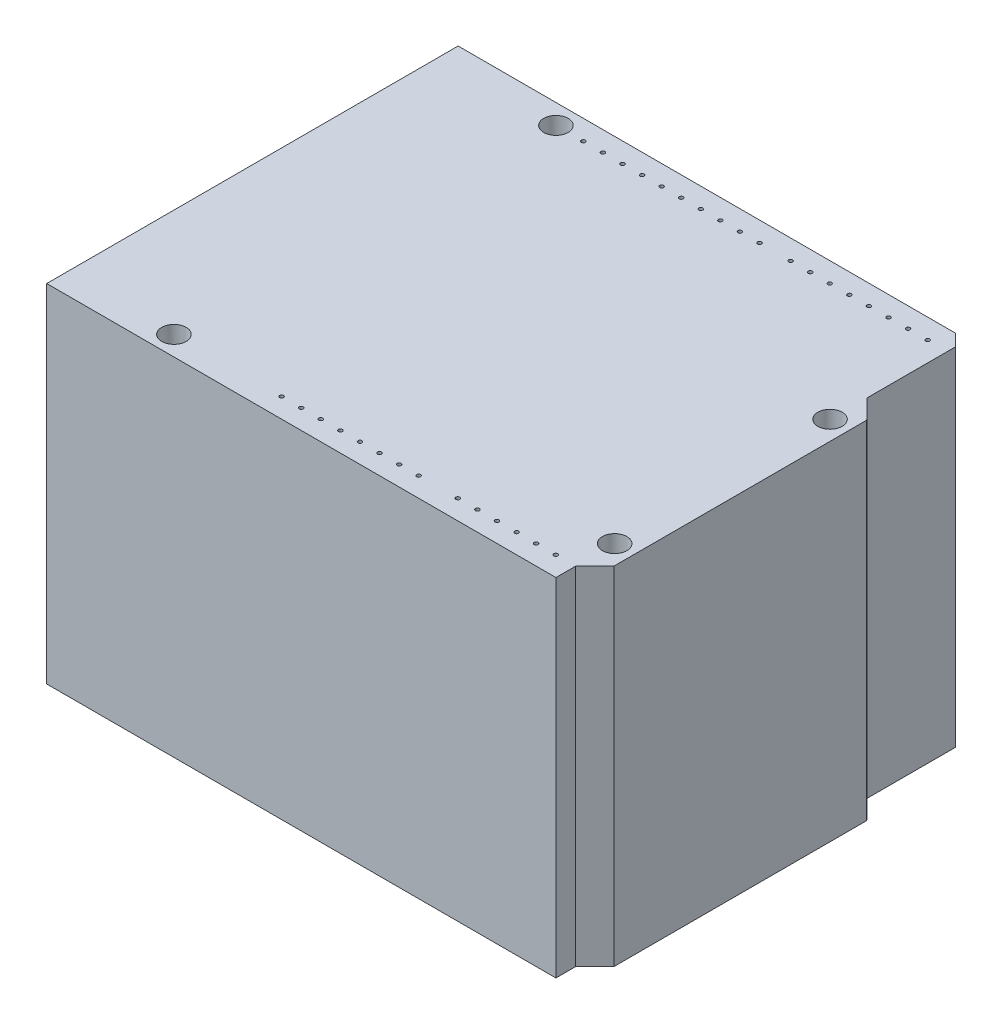
SolidWorks part; units mm, degrees
ref_plane "Alzado" through (0, 0, 0) normal (0, 0, 1) x (1, 0, 0)
ref_plane "Planta" through (0, 0, 0) normal (0, 1, 0) x (1, 0, 0)
ref_plane "Vista lateral" through (0, 0, 0) normal (1, 0, 0) x (0, 0, -1)
sketch "Board" plane through (0, 0, 0) normal (0, 1, 0) x (1, 0, 0)
  line L0 (68.55, 37.846) -> (68.55, 5.08)
  line L1 (66.07, 0) -> (0, 0)
  line L2 (66.07, 51.8137) -> (66.07, 40.386)
  line L3 (66.07, 0) -> (66.07, 2.54)
  line L4 (66.07, 40.386) -> (68.55, 37.846)
  line L5 (68.55, 5.08) -> (66.07, 2.54)
  line L6 (0, 0) -> (0, 53.3785)
  line L7 (64.5052, 53.3785) -> (0, 53.3785)
  line L8 (66.07, 51.8137) -> (64.5052, 53.3785)
sketch "Drills" plane through (0, 0, 0) normal (0, 1, 0) x (1, 0, 0)
  line L0 (13.97, 2.54) -> (63.5, 2.54) construction
  line L2 (15.27, 50.8) -> (63.5, 50.8) construction
  circle A0 centre (15.27, 50.8) radius 1.5875
  circle A1 centre (66.07, 35.56) radius 1.5875
  circle A2 centre (66.07, 7.62) radius 1.5875
  circle A3 centre (13.97, 2.54) radius 1.5875
sketch "Pinout" plane through (0, 0, 0) normal (0, 1, 0) x (1, 0, 0)
  circle A0 centre (63.5, 2.54) radius 0.254
  circle A1 centre (60.96, 2.54) radius 0.254
  circle A2 centre (58.42, 2.54) radius 0.254
  circle A3 centre (55.88, 2.54) radius 0.254
  circle A4 centre (53.34, 2.54) radius 0.254
  circle A5 centre (50.8, 2.54) radius 0.254
  circle A6 centre (45.72, 2.54) radius 0.254
  circle A7 centre (43.18, 2.54) radius 0.254
  circle A8 centre (40.64, 2.54) radius 0.254
  circle A9 centre (38.1, 2.54) radius 0.254
  circle A10 centre (35.56, 2.54) radius 0.254
  circle A11 centre (33.02, 2.54) radius 0.254
  circle A12 centre (30.48, 2.54) radius 0.254
  circle A13 centre (27.94, 2.54) radius 0.254
  circle A14 centre (63.5, 50.8) radius 0.254
  circle A15 centre (60.96, 50.8) radius 0.254
  circle A16 centre (58.42, 50.8) radius 0.254
  circle A17 centre (55.88, 50.8) radius 0.254
  circle A18 centre (53.34, 50.8) radius 0.254
  circle A19 centre (50.8, 50.8) radius 0.254
  circle A20 centre (48.26, 50.8) radius 0.254
  circle A21 centre (45.72, 50.8) radius 0.254
  circle A22 centre (41.686, 50.8) radius 0.254
  circle A23 centre (39.146, 50.8) radius 0.254
  circle A24 centre (36.606, 50.8) radius 0.254
  circle A25 centre (34.066, 50.8) radius 0.254
  circle A26 centre (31.526, 50.8) radius 0.254
  circle A27 centre (28.986, 50.8) radius 0.254
  circle A28 centre (26.446, 50.8) radius 0.254
  circle A29 centre (23.906, 50.8) radius 0.254
  circle A30 centre (21.366, 50.8) radius 0.254
  circle A31 centre (18.826, 50.8) radius 0.254
  dimension "D1" = 8
  dimension "D2" = 10
  dimension "D3" = 6
  dimension "D4" = 8
extrude "Saliente-Extruir1" add sketch "Board" along normal blind 45
extrude "Cortar-Extruir1" cut sketch "Drills" along normal through all
extrude "Cortar-Extruir2" cut sketch "Pinout" along normal through all
